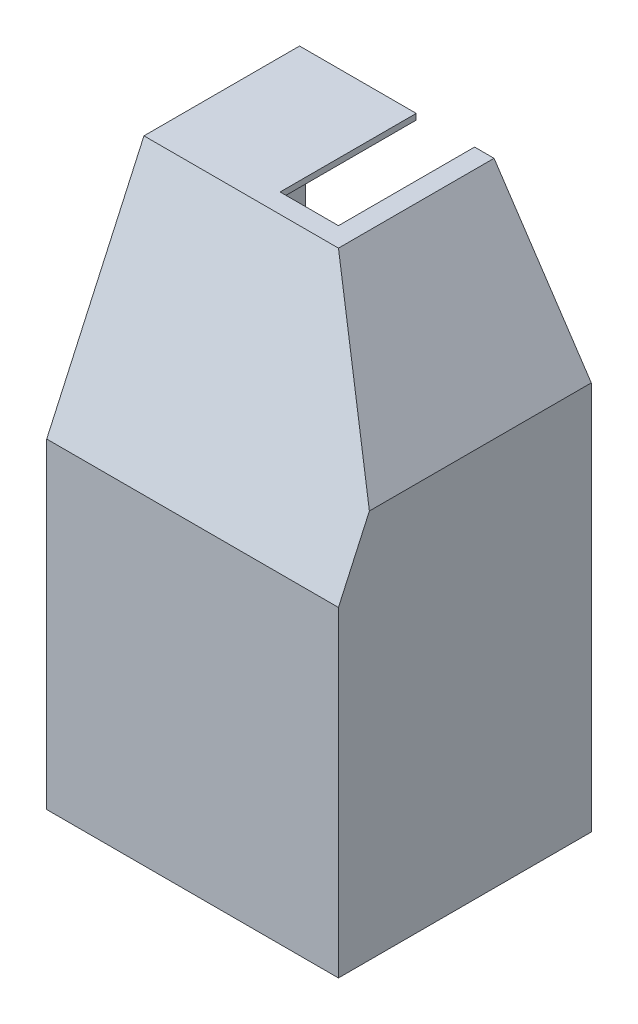
SolidWorks part; units mm, degrees
ref_plane "前视基准面" through (0, 0, 0) normal (0, 0, 1) x (1, 0, 0)
ref_plane "上视基准面" through (0, 0, 0) normal (0, 1, 0) x (1, 0, 0)
ref_plane "右视基准面" through (0, 0, 0) normal (1, 0, 0) x (0, 0, -1)
other "Configuration Table"
sketch "草图2" plane through (0, 0, 0) normal (0, 0, 1) x (1, 0, 0)
  line L1 (-75, 280) -> (-75, 5)
  line L2 (-75, 5) -> (75, 5)
  line L3 (75, 5) -> (75, 205)
  line L4 (75, 205) -> (25, 280)
  line L6 (25, 280) -> (-75, 280)
  line L7 (-70, 0) -> (70, 0) construction
  line L9 (-80, 275) -> (-80, 10) construction
  line L13 (80, 210) -> (40, 270) construction
  point P0 (25, 278.6903)
  dimension "D1" = 275
  dimension "D2" = 150
  dimension "D3" = 5
  dimension "D4" = 5
  dimension "D5" = 100
  dimension "D6" = 0
extrude "凸台-拉伸1" add sketch "草图2" along normal blind 130
chamfer "倒角1" distance 50 distance2 110 1 edges at (-25, 280, 130)
shell "抽壳1" thickness 3
sketch "草图3" plane through (0, 280, 0) normal (0, 1, 0) x (1, 0, 0)
  line L0 (15, 0) -> (15, -70)
  line L1 (25, 0) -> (-75, 0) construction
  line L2 (15, -70) -> (-15, -70)
  line L3 (-15, -70) -> (-15, 0)
  line L4 (-15, 0) -> (15, 0)
  line L5 (25, -80) -> (25, 0) construction
  dimension "D1" = 30
  dimension "D2" = 70
  dimension "D3" = 10
extrude "切除-拉伸1" cut sketch "草图3" against normal blind 3
